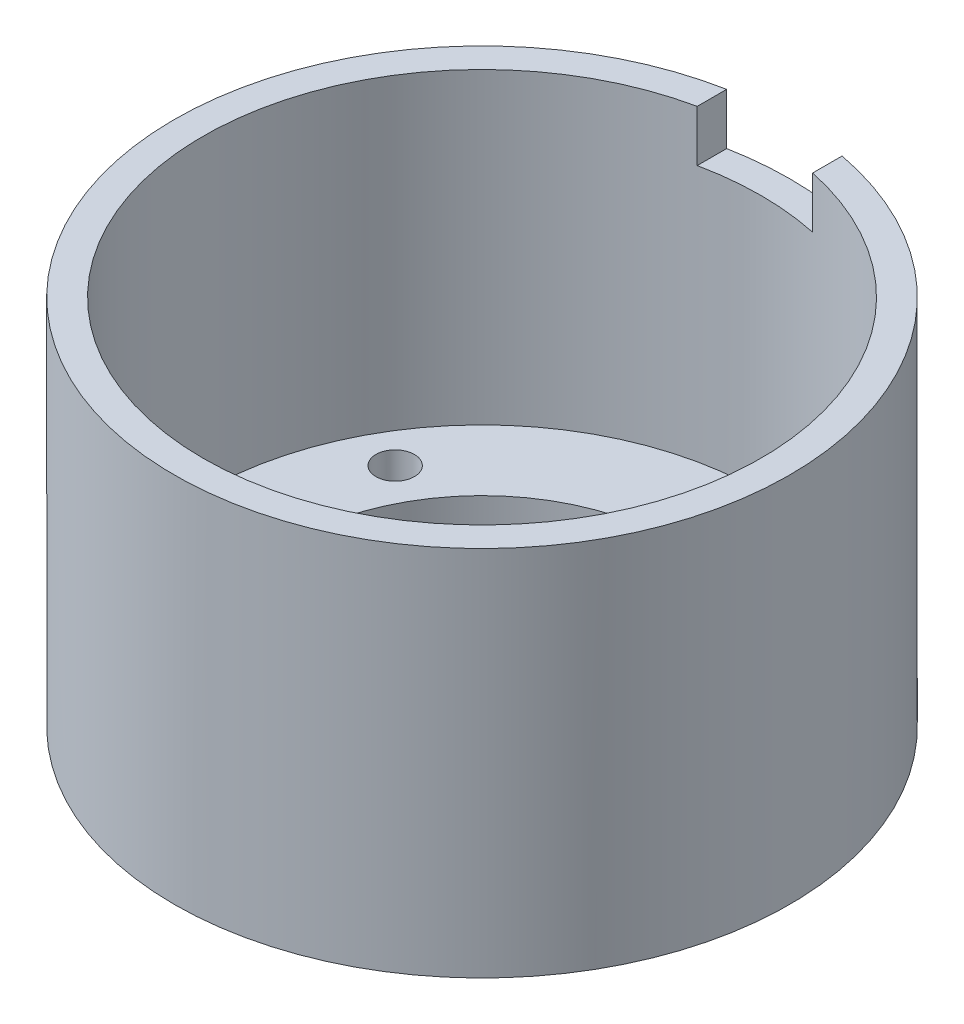
SolidWorks part; units mm, degrees
ref_plane "Front Plane" through (0, 0, 0) normal (0, 0, 1) x (1, 0, 0)
ref_plane "Top Plane" through (0, 0, 0) normal (0, 1, 0) x (1, 0, 0)
ref_plane "Right Plane" through (0, 0, 0) normal (1, 0, 0) x (0, 0, -1)
sketch "Sketch1" plane through (0, 0, 0) normal (0, 1, 0) x (1, 0, 0)
  circle A0 centre (0, 0) radius 24
  circle A1 centre (0, 0) radius 21.75
  dimension "D1" = 43.5
  dimension "D2" = 48
extrude "Boss-Extrude1" add sketch "Sketch1" along normal blind 24
sketch "Sketch2" plane through (0, 0, 0) normal (0, -1, 0) x (1, 0, 0)
  circle A0 centre (0, 0) radius 24
  circle A1 centre (0, 0) radius 15
  circle A2 centre (0, 0) radius 24 construction
  dimension "D1" = 30
extrude "Boss-Extrude2" add sketch "Sketch2" along normal blind 5
sketch "Sketch3" plane through (0, -5, 0) normal (0, -1, 0) x (1, 0, 0)
  circle A0 centre (0, 0) radius 18.5 construction
  circle A1 centre (0, 18.5) radius 2.5
  circle A2 centre (16.0215, -9.25) radius 2.5
  circle A3 centre (-16.0215, -9.25) radius 2.5
  dimension "D1" = 37
  dimension "D3" = 5
  dimension "D2" = 3
extrude "Cut-Extrude1" cut sketch "Sketch3" against normal blind 2
sketch "Sketch4" plane through (0, -3, 0) normal (0, -1, 0) x (1, 0, 0)
  circle A0 centre (0, 18.5) radius 1.5
  circle A1 centre (16.0215, -9.25) radius 1.5
  circle A2 centre (-16.0215, -9.25) radius 1.5
  dimension "D1" = 3
extrude "Cut-Extrude2" cut sketch "Sketch4" against normal through all
ref_plane "Plane1" through (0, 0, -24) normal (0, 0, -1) x (-1, 0, 0)
sketch "Sketch5" plane through (0, 0, -24) normal (0, 0, -1) x (-1, 0, 0)
  line L0 (24, 24) -> (-24, 24) construction
  line L1 (-4.5, 24) -> (4.5, 24)
  line L2 (-4.5, 24) -> (-4.5, 20)
  line L3 (-4.5, 20) -> (4.5, 20)
  line L4 (4.5, 24) -> (4.5, 20)
  point P6 (0, 20)
  dimension "D1" = 9
  dimension "D2" = 4
extrude "Cut-Extrude3" cut sketch "Sketch5" against normal up to surface (2.7206 mm away)
sketch "Sketch6" plane through (0, 24, 0) normal (0, 1, 0) x (1, 0, 0)
  line L1 (-16, -16) -> (16, -16) construction
  line L2 (-16, -16) -> (-16, 16) construction
  line L3 (-16, 16) -> (16, 16) construction
  line L4 (16, -16) -> (16, 16) construction
  line L5 (-16, -16) -> (16, 16) construction
  line L6 (-16, 16) -> (16, -16) construction
  circle A10 centre (16, 16) radius 1.5
  circle A11 centre (-16, 16) radius 1.5
  circle A12 centre (-16, -16) radius 1.5
  circle A13 centre (16, -16) radius 1.5
  dimension "D2" = 3
  dimension "D1" = 32
